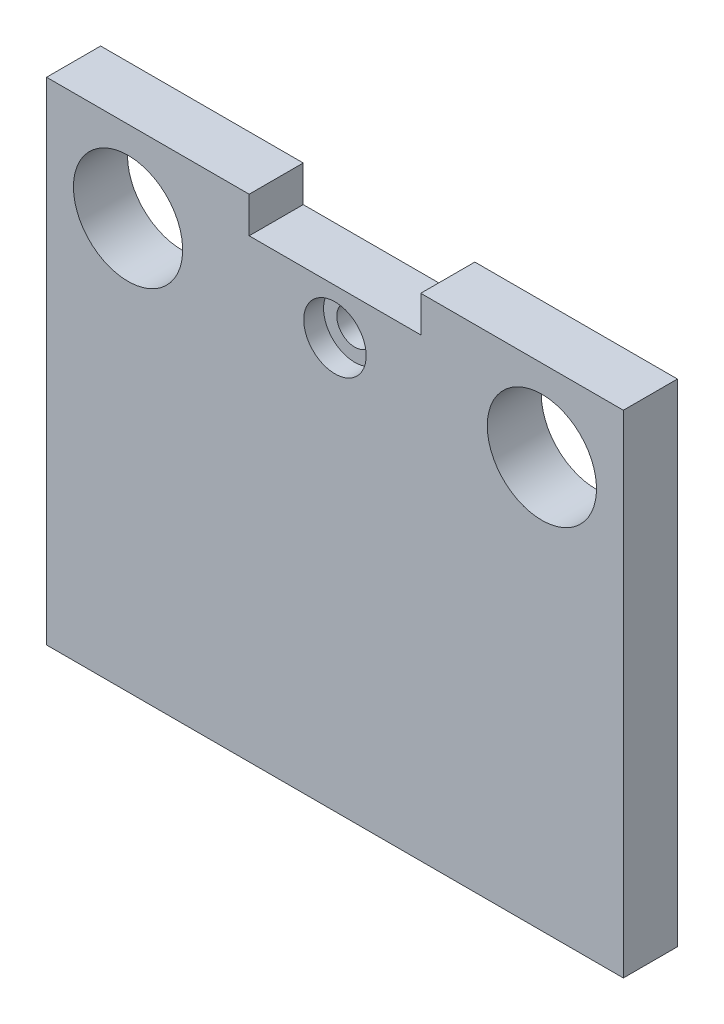
SolidWorks part; units mm, degrees
material "Balsa"
ref_plane "Front Plane" through (0, 0, 0) normal (0, 0, 1) x (1, 0, 0)
ref_plane "Top Plane" through (0, 0, 0) normal (0, 1, 0) x (1, 0, 0)
ref_plane "Right Plane" through (0, 0, 0) normal (1, 0, 0) x (0, 0, -1)
sketch "Sketch1" plane through (0, 0, 0) normal (0, 0, 1) x (1, 0, 0)
  line L1 (0, 0) -> (203.2, 0)
  line L2 (0, 0) -> (0, 304.8)
  line L3 (0, 304.8) -> (203.2, 304.8)
  line L4 (203.2, 0) -> (203.2, 304.8)
  dimension "D1" = 203.2
  dimension "D2" = 304.8
extrude "Boss-Extrude1" add sketch "Sketch1" along normal blind 19.05
sketch "Esquisse1" plane through (0, 0, 19.05) normal (0, 0, 1) x (1, 0, 0)
  line L0 (151.2, 219.075) -> (52, 219.075) construction
  line L1 (52, 219.075) -> (52, 168.275) construction
  line L2 (52, 168.275) -> (151.2, 168.275) construction
  line L3 (151.2, 168.275) -> (151.2, 219.075) construction
  line L4 (151.2, 219.075) -> (151.2, 79.375) construction
  line L5 (151.2, 79.375) -> (151.2, 28.575) construction
  line L6 (151.2, 28.575) -> (52, 28.575) construction
  line L7 (52, 28.575) -> (52, 79.375) construction
  line L8 (52, 79.375) -> (151.2, 79.375) construction
  line L9 (203.2, 0) -> (203.2, 304.8) construction
  line L10 (0, 0) -> (203.2, 0) construction
  circle A0 centre (52, 219.075) radius 3.937
  circle A1 centre (151.2, 219.075) radius 3.937
  circle A2 centre (151.2, 168.275) radius 3.937
  circle A3 centre (52, 168.275) radius 3.937
  circle A4 centre (52, 79.375) radius 3.937
  circle A5 centre (151.2, 79.375) radius 3.937
  circle A6 centre (151.2, 28.575) radius 3.937
  circle A7 centre (52, 28.575) radius 3.937
  dimension "D1" = 7.874
  dimension "D2" = 52
  dimension "D3" = 28.575
  dimension "D4" = 139.7
  dimension "D5" = 99.2
  dimension "D6" = 50.8
extrude "Enlèv. mat.-Extru.1" [suppressed] cut sketch "Esquisse1" against normal through all
sketch "Esquisse2" plane through (0, 0, 0) normal (0, 0, -1) x (-1, 0, 0)
  line L0 (0, 304.8) -> (0, 0) construction
  line L1 (-203.2, 304.8) -> (0, 304.8)
  line L2 (-203.2, 304.8) -> (-203.2, 266.7)
  line L3 (-203.2, 266.7) -> (0, 266.7)
  line L4 (0, 304.8) -> (0, 266.7)
  dimension "D1" = 38.1
extrude "Enlèv. mat.-Extru.2" cut sketch "Esquisse2" against normal through all
sketch "Esquisse3" plane through (0, 0, 0) normal (0, 0, -1) x (-1, 0, 0)
  line L0 (0, 266.7) -> (0, 0) construction
  line L1 (-203.2, 266.7) -> (0, 266.7)
  line L2 (-203.2, 266.7) -> (-203.2, 173.228)
  line L3 (-203.2, 173.228) -> (0, 173.228)
  line L4 (0, 266.7) -> (0, 173.228)
  dimension "D1" = 93.472
extrude "Enlèv. mat.-Extru.3" cut sketch "Esquisse3" against normal through all
sketch "Esquisse5" plane through (0, 0, 0) normal (0, 0, -1) x (-1, 0, 0)
  line L0 (-174.498, 144.526) -> (-174.498, 173.228) construction
  line L1 (-203.2, 173.228) -> (0, 173.228) construction
  line L2 (-174.498, 144.526) -> (-203.2, 144.526) construction
  line L3 (-203.2, 0) -> (-203.2, 173.228) construction
  line L4 (-28.702, 144.526) -> (-28.702, 173.228) construction
  line L5 (-28.702, 144.526) -> (0, 144.526) construction
  line L6 (0, 173.228) -> (0, 0) construction
  circle A0 centre (-174.498, 144.526) radius 19.2405
  circle A1 centre (-28.702, 144.526) radius 19.2405
  dimension "D1" = 38.481
  dimension "D2" = 28.702
extrude "Enlèv. mat.-Extru.5" cut sketch "Esquisse5" against normal through all
sketch "Esquisse4" [suppressed] plane through (0, 0, 0) normal (0, 0, -1) x (-1, 0, 0)
  line L0 (0, 173.228) -> (0, 0) construction
  line L1 (-203.2, 173.228) -> (0, 173.228)
  line L2 (-203.2, 173.228) -> (-203.2, 97.028)
  line L3 (-203.2, 97.028) -> (0, 97.028)
  line L4 (0, 173.228) -> (0, 97.028)
  dimension "D1" = 80.63
extrude "Enlèv. mat.-Extru.4" [suppressed] cut sketch "Esquisse4" against normal through all
sketch "Esquisse6" [suppressed] plane through (0, 0, 0) normal (0, 0, -1) x (-1, 0, 0)
  line L0 (-155.2575, 144.526) -> (-47.9425, 144.526) construction
  line L1 (-125.1712, 168.0972) -> (-78.0288, 120.9548) construction
  line L2 (-125.1712, 120.9548) -> (-78.0288, 120.9548) construction
  line L3 (-125.1712, 120.9548) -> (-125.1712, 168.0972) construction
  line L4 (-125.1712, 168.0972) -> (-78.0288, 168.0972) construction
  line L5 (-78.0288, 120.9548) -> (-78.0288, 168.0972) construction
  line L6 (-101.6, 40.2261) -> (-101.6, 144.526) construction
  line L7 (-101.6, 144.526) -> (-101.6, 248.8259) construction
  line L8 (-203.2, 173.228) -> (0, 173.228) construction
  circle A0 centre (-174.498, 144.526) radius 19.2405 construction
  circle A1 centre (-28.702, 144.526) radius 19.2405 construction
  circle A2 centre (-101.6, 144.526) radius 15.875
  circle A3 centre (-125.1712, 168.0972) radius 2.5
  circle A4 centre (-78.0288, 168.0972) radius 2.5
  circle A5 centre (-78.0288, 120.9548) radius 2.5
  circle A6 centre (-125.1712, 120.9548) radius 2.5
  point P14 (-101.6, 144.526)
  point P20 (-101.6, 144.526)
extrude "Enlèv. mat.-Extru.6" [suppressed] cut sketch "Esquisse6" against normal up to next
sketch "Esquisse9" plane through (0, 0, 19.05) normal (0, 0, 1) x (1, 0, 0)
  line L0 (47.9425, 144.526) -> (155.2575, 144.526) construction
  circle A0 centre (28.702, 144.526) radius 19.2405 construction
  circle A1 centre (174.498, 144.526) radius 19.2405 construction
  circle A2 centre (101.6, 144.526) radius 10.9982
  dimension "D1" = 21.9964
extrude "Enlèv. mat.-Extru.9" cut sketch "Esquisse9" against normal blind 6.985
sketch "Esquisse10" plane through (0, 0, 12.065) normal (0, 0, 1) x (1, 0, 0)
  circle A0 centre (101.6, 144.526) radius 6.35
  dimension "D1" = 12.7
extrude "Enlèv. mat.-Extru.10" cut sketch "Esquisse10" against normal through all
sketch "Esquisse11" plane through (0, 0, 0) normal (0, 0, -1) x (-1, 0, 0)
  line L0 (-203.2, 173.228) -> (0, 173.228) construction
  line L1 (-131.826, 173.228) -> (-71.374, 173.228)
  line L2 (-131.826, 173.228) -> (-131.826, 160.528)
  line L3 (-131.826, 160.528) -> (-71.374, 160.528)
  line L4 (-71.374, 173.228) -> (-71.374, 160.528)
  point P6 (-101.6, 173.228)
  point P8 (-101.6, 160.528)
  dimension "D1" = 12.7
  dimension "D2" = 60.452
extrude "Enlèv. mat.-Extru.11" cut sketch "Esquisse11" against normal blind 19.05
